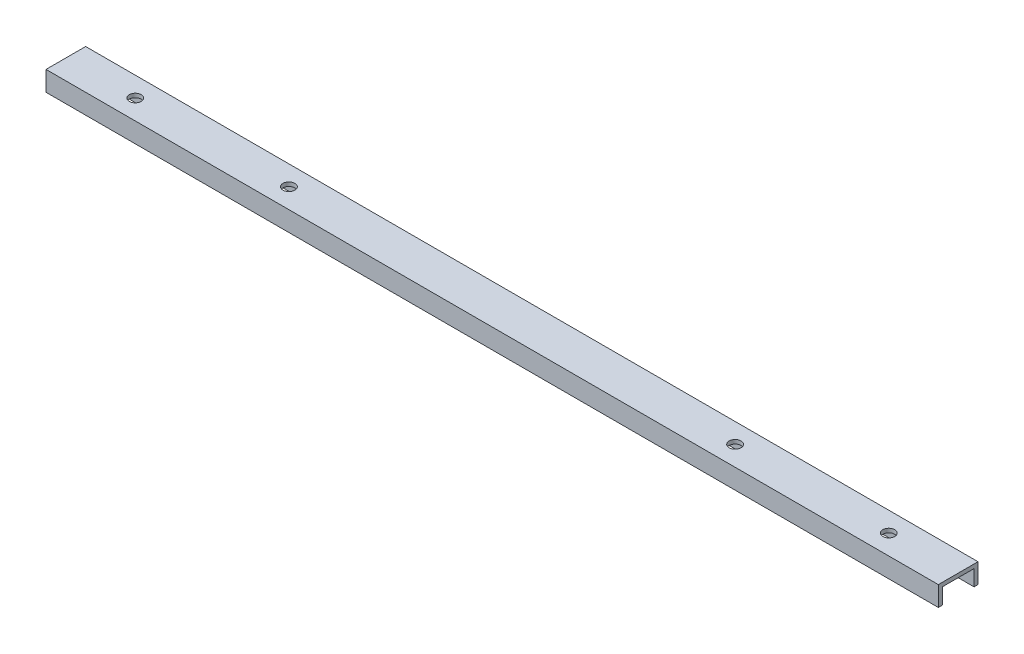
SolidWorks part; units mm, degrees
ref_plane "Спереди" through (0, 0, 0) normal (0, 0, 1) x (1, 0, 0)
ref_plane "Сверху" through (0, 0, 0) normal (0, 1, 0) x (1, 0, 0)
ref_plane "Справа" through (0, 0, 0) normal (1, 0, 0) x (0, 0, -1)
sketch "Эскиз1" plane through (0, 0, 0) normal (1, 0, 0) x (0, 0, -1)
  line L0 (-20, 0) -> (-20, 10)
  line L1 (-20, 10) -> (0, 10)
  line L2 (0, 10) -> (0, 0)
  line L3 (0, 0) -> (-2, 0)
  line L4 (-2, 0) -> (-2, 8)
  line L5 (-2, 8) -> (-18, 8)
  line L6 (-18, 8) -> (-18, 0)
  line L7 (-18, 0) -> (-20, 0)
  dimension "D1" = 20
  dimension "D2" = 10
  dimension "D3" = 8
  dimension "D4" = 2
extrude "Бобышка-Вытянуть1" add sketch "Эскиз1" along normal blind 450
sketch "Эскиз2" plane through (0, 10, 0) normal (0, 1, 0) x (1, 0, 0)
  line L0 (450, 0) -> (450, -20) construction
  line L1 (450, 0) -> (0, 0) construction
  line L2 (0, 0) -> (0, -20) construction
  circle A0 centre (415, -10) radius 3
  circle A1 centre (337.5, -10) radius 3
  circle A2 centre (35, -10) radius 3
  circle A3 centre (112.5, -10) radius 3
  dimension "D1" = 6
  dimension "D5" = 35
  dimension "D2" = 35
  dimension "D3" = 77.5
  dimension "D4" = 10
  dimension "D6" = 77.5
extrude "Вырез-Вытянуть1" cut sketch "Эскиз2" against normal up to surface (2 mm away) up to face at (225, 8, 10)
